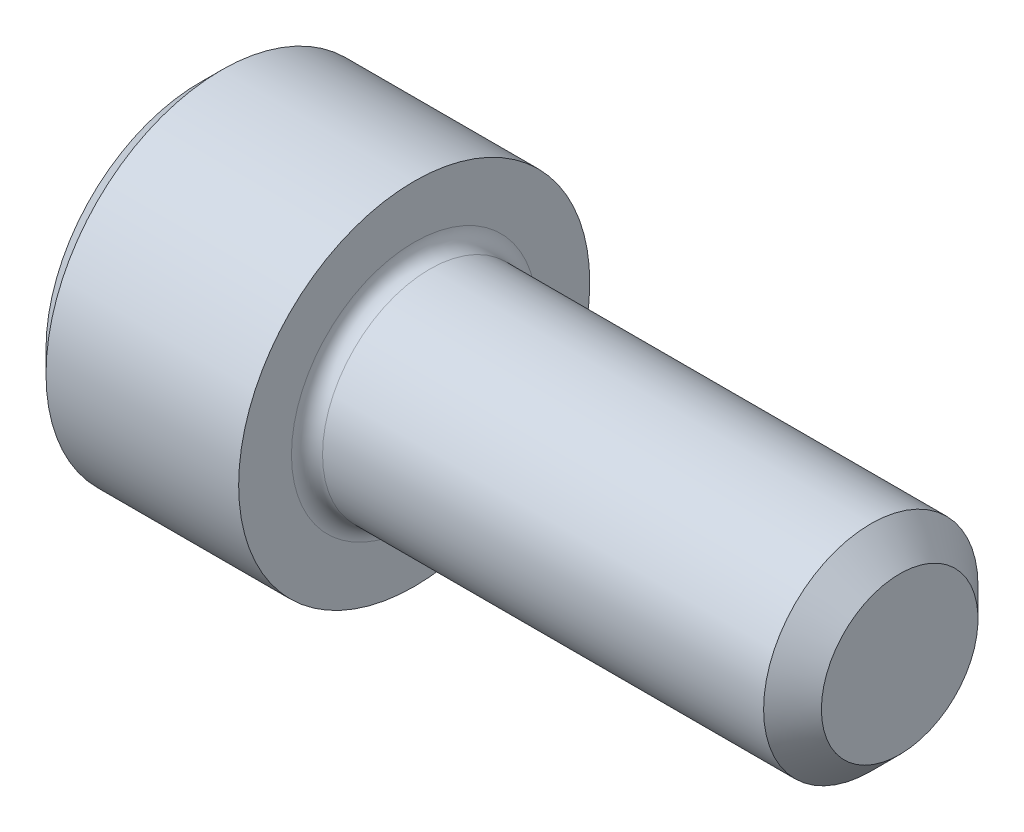
SolidWorks part; units mm, degrees
material "Alloy Steel"
ref_plane "Plane1" through (0, 0, 0) normal (0, 0, 1) x (1, 0, 0)
ref_plane "Plane2" through (0, 0, 0) normal (0, 1, 0) x (1, 0, 0)
ref_plane "Plane3" through (0, 0, 0) normal (1, 0, 0) x (0, 0, -1)
revolve "Base-Revolve" add sketch "BodySke"
sketch "BodySke" plane through (0, 0, 0) normal (0, 0, 1) x (1, 0, 0)
  line L0 (0, 0) -> (0, 2.5146)
  line L1 (0.3556, 2.8702) -> (3.5052, 2.8702)
  line L2 (3.5052, 2.8702) -> (3.5052, 1.7526)
  line L3 (3.5052, 1.7526) -> (10.9703, 1.7526)
  line L4 (11.4427, 1.2802) -> (11.4427, 0)
  line L5 (11.4427, 0) -> (0, 0)
  line L6 (-31.75, 0) -> (127, 0) construction
  line L7 (0, 2.5146) -> (0.3556, 2.8702)
  line L8 (11.4427, 1.2802) -> (10.9703, 1.7526)
  line L9 (0, -2.5146) -> (0.3556, -2.8702) construction
  line L10 (11.4427, -1.2802) -> (10.9703, -1.7526) construction
  line L11 (4.2977, 9.525) -> (4.2977, 3.175) construction
  line L12 (3.5052, 9.525) -> (3.5052, 3.175) construction
  line L13 (-26.6573, 9.525) -> (-26.6573, 3.175) construction
  dimension "Diameter" = 3.5052
  dimension "Head_ht" = 3.5052
  dimension "Length" = 7.9375
  dimension "Body_ch_ang" = 45
  dimension "Head_dia" = 5.7404
  dimension "Head_ch_ang" = 45
  dimension "Head_side_ht" = 3.1496
  dimension "Minor_dia" = 2.5603
  dimension "Advance" = 0.7925
  dimension "Thread_nom" = 7.9375
  dimension "Thread_length" = 38.1
cosmetic thread "ThreadCosmetic"
fillet "Fillet1" radius 0.254 1 edges at (3.5052, 0, 1.7526)
sketch "Sketch2" plane through (0, 0, 0) normal (0, 0, 1) x (1, 0, 0)
  line L0 (0, 1.3843) -> (1.6256, 1.3843)
  line L1 (1.6256, 1.3843) -> (2.4248, 0)
  line L2 (-31.75, 0) -> (127, 0) construction
  line L3 (2.4248, 0) -> (0, 0)
  line L4 (0, 0) -> (0, 1.3843)
  line L5 (0, 2.5146) -> (0, -2.5146) construction
  line L6 (0, 0) -> (47.625, 0) construction
  line L7 (3.5052, -2.8702) -> (3.5052, 2.8702) construction
  dimension "D1" = 1.3843
  dimension "D2" = 60
  dimension "Wall_thickness" = 1.8796
revolve "Hex-PreBroach" cut sketch "Sketch2" angle 360 about L6
sketch "Sketch3" plane through (0, 0, 0) normal (-1, 0, 0) x (0, 0.5, 0.866)
  line L0 (0.7992, 1.3843) -> (-0.7992, 1.3843)
  line L1 (-0.7992, 1.3843) -> (-1.5985, 0)
  line L2 (0.7992, 1.3843) -> (1.5985, 0)
  line L3 (0.7992, -1.3843) -> (1.5985, 0)
  line L4 (0.7992, -1.3843) -> (-0.7992, -1.3843)
  line L5 (-0.7992, -1.3843) -> (-1.5985, 0)
  dimension "D1" = 1.3843
  dimension "D2" = 1.3843
  dimension "Hex_size" = 2.7686
extrude "Hex" cut sketch "Sketch3" against normal blind 1.6256
sketch "Sketch4" plane through (0, 0, 0) normal (-1, 0, 0) x (0, 0, 1)
  line L0 (0, 0) -> (1.7399, 0)
  line L1 (0, 0) -> (6.1484, 3.5498) construction
  line L2 (0, 0) -> (0.8699, 1.5068)
  line L3 (1.4457, 0.3947) -> (1.6607, 0.5189)
  line L4 (1.0647, 1.0546) -> (1.2797, 1.1788)
  arc A0 (1.4457, 0.3947) -> (1.0647, 1.0546) centre (0, 0) ccw
  arc A1 (1.7399, 0) -> (1.6607, 0.5189) centre (0, 0) ccw
  arc A2 (0.8699, 1.5068) -> (1.2797, 1.1788) centre (0, 0) cw
  dimension "D1" = 30
  dimension "Spline_n_dim" = 2.9972
  dimension "Spline_m_dim" = 3.4798
  dimension "D2" = 60
  dimension "D3" = 0.381
  dimension "Spline_p_dim" = 0.762
extrude "Spline" [suppressed] cut sketch "Sketch4" against normal blind 1.6256
pattern_circular "CirPattern1" [suppressed] count 6 every 60
sketch "Sketch5" plane through (0, 0, 0) normal (0, 0, 1) x (1, 0, 0)
  line L0 (-31.75, 0) -> (127, 0) construction
  line L2 (0, 2.5146) -> (0, -2.5146) construction
  circle A0 centre (1.27, 0) radius 0.4445
  dimension "Drilled_hole_dia" = 0.889
  dimension "Drilled_hole_loc" = 1.27
extrude "Hole" [suppressed] cut sketch "Sketch5" against normal through all and the other way through all
pattern_circular "Drilled-4" [suppressed] count 2 every 60
pattern_circular "Drilled-6" [suppressed] count 3 every 60
sketch "ThdSchSke" plane through (0, 0, 0) normal (0, 0, 1) x (1, 0, 0)
  line L0 (4.2977, -1.2802) -> (3.9669, -1.7526)
  line L1 (4.2977, -1.2802) -> (4.6285, -1.7526)
  line L2 (4.6285, -1.7526) -> (4.6285, -2.1908)
  line L3 (-3.175, 0) -> (5.1513, 0) construction
  line L5 (4.6285, -2.1908) -> (3.9669, -2.1908)
  line L6 (3.9669, -2.1908) -> (3.9669, -1.7526)
  line L7 (0, 2.5146) -> (0, -2.5146) construction
  dimension "Thread_minor" = 2.5603
  dimension "Diameter" = 3.5052
  dimension "Start" = 4.2977
  dimension "SideAngle" = 55
  dimension "VeeAngle" = 70
  dimension "Overcut" = 4.3815
revolve "ThreadSchematic" [suppressed] cut sketch "ThdSchSke" angle 360 about L3
pattern_linear "ThdSchPat" [suppressed]
equation "\"D2@Sketch3\" = \"Hex_size@Sketch3\" / 2"
equation "\"D1@Sketch3\" = \"Hex_size@Sketch3\" / 2"
equation "\"D1@Sketch2\" = \"Hex_size@Sketch3\" / 2"
equation "\"D3@Sketch4\" = \"Spline_p_dim@Sketch4\" / 2"
equation "\"Thread_minor@ThreadCosmetic\"  =  \"Minor_dia@BodySke\""
equation "\"D2@CirPattern1\" = 360 / \"Num_teeth@CirPattern1\""
equation "\"Wall_thickness@Sketch2\" = \"Head_ht@BodySke\" - \"Key_eng@Hex\""
equation "\"Thread_length@ThreadCosmetic\" = ((sgn( (\"Length@BodySke\" - \"Advance@BodySke\" ) - \"Thread_nom@BodySke\" )-1)*( (\"Length@BodySke\" - \"Advance@BodySke\" ) - \"Thread_nom@BodySke\" ))/-2+ \"Thread_nom@BodySke\""
equation "\"Thread_minor@ThdSchSke\" = \"Minor_dia@BodySke\""
equation "\"Diameter@ThdSchSke\" = \"Diameter@BodySke\""
equation "\"Overcut@ThdSchSke\" = \"Diameter@BodySke\" * 1.25"
equation "\"Start@ThdSchSke\" = \"Head_ht@BodySke\" + \"Length@BodySke\" - \"Thread_length@ThreadCosmetic\"  '---Non-countersunk---"
equation "\"Num_threads@ThdSchPat\" = int( \"Thread_length@ThreadCosmetic\" / \"Advance@BodySke\" + 0.999 )  + 1"
equation "\"Advance@ThdSchPat\" = \"Thread_length@ThreadCosmetic\" /  (\"Num_threads@ThdSchPat\" - 1) 'relax it"
equation "\"Num_threads@ThdSchPat\" = \"Num_threads@ThdSchPat\" - sgn( \"Num_threads@ThdSchPat\" - 1) '---chamfered tips only---"
